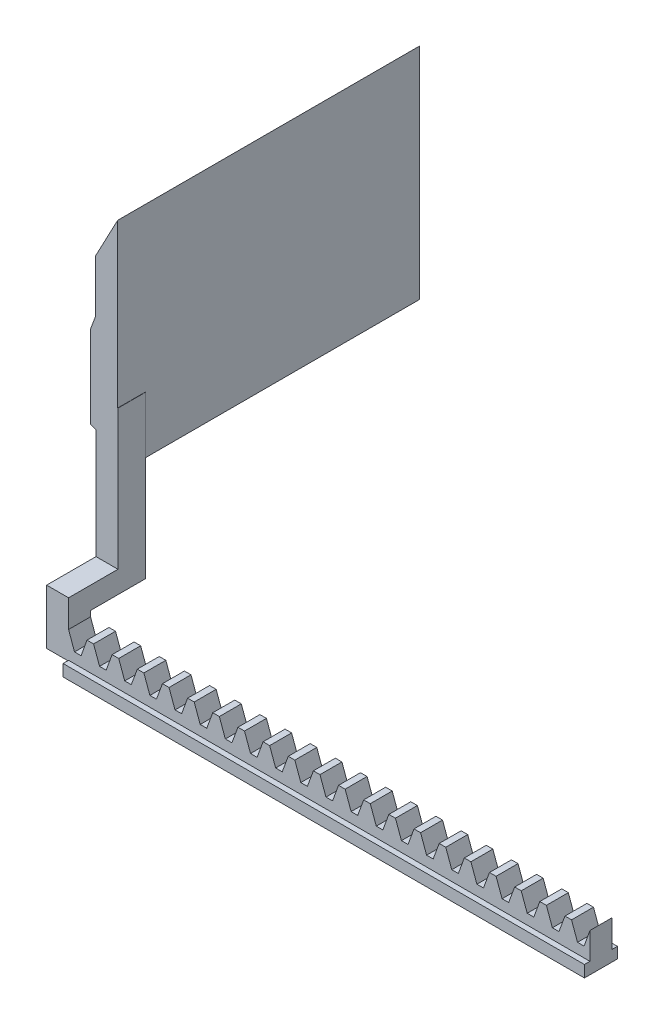
SolidWorks part; units mm, degrees
ref_plane "Plan de face" through (0, 0, 0) normal (0, 0, 1) x (1, 0, 0)
ref_plane "Plan de dessus" through (0, 0, 0) normal (0, 1, 0) x (1, 0, 0)
ref_plane "Plan de droite" through (0, 0, 0) normal (1, 0, 0) x (0, 0, -1)
sketch "Esquisse1" plane through (0, 0, 0) normal (0, 0, 1) x (1, 0, 0)
  line L0 (-0.6, 0) -> (0.6, 0)
  line L1 (0.6, 0) -> (1.6919, 3)
  line L2 (-0.6, 0) -> (-1.6919, 3)
  line L3 (-1.6919, 3) -> (-2.8919, 3)
  line L4 (1.6919, 3) -> (2.8919, 3)
  line L5 (0, 0) -> (0, 2.6442) construction
  line L6 (-47.5, -4) -> (47.5, -4)
  line L7 (3.9838, 0) -> (2.8919, 3)
  line L8 (5.1838, 0) -> (6.2757, 3)
  line L9 (3.9838, 0) -> (5.1838, 0)
  line L10 (8.5676, 0) -> (7.4757, 3)
  line L11 (9.7676, 0) -> (10.8596, 3)
  line L12 (8.5676, 0) -> (9.7676, 0)
  line L13 (13.1515, 0) -> (12.0596, 3)
  line L14 (14.3515, 0) -> (15.4434, 3)
  line L15 (13.1515, 0) -> (14.3515, 0)
  line L16 (17.7353, 0) -> (16.6434, 3)
  line L17 (18.9353, 0) -> (20.0272, 3)
  line L18 (17.7353, 0) -> (18.9353, 0)
  line L19 (22.3191, 0) -> (21.2272, 3)
  line L20 (23.5191, 0) -> (24.611, 3)
  line L21 (22.3191, 0) -> (23.5191, 0)
  line L22 (26.9029, 0) -> (25.811, 3)
  line L23 (28.1029, 0) -> (29.1948, 3)
  line L24 (26.9029, 0) -> (28.1029, 0)
  line L25 (31.4867, 0) -> (30.3948, 3)
  line L26 (32.6867, 0) -> (33.7787, 3)
  line L27 (31.4867, 0) -> (32.6867, 0)
  line L28 (36.0706, 0) -> (34.9787, 3)
  line L29 (37.2706, 0) -> (38.3625, 3)
  line L30 (36.0706, 0) -> (37.2706, 0)
  line L31 (40.6544, 0) -> (39.5625, 3)
  line L32 (41.8544, 0) -> (42.9463, 3)
  line L33 (40.6544, 0) -> (41.8544, 0)
  line L34 (45.2382, 0) -> (44.1463, 3)
  line L35 (46.4382, 0) -> (47.5, 3.0001)
  line L36 (45.2382, 0) -> (46.4382, 0)
  line L37 (-44.1463, 3) -> (-42.9463, 3)
  line L38 (-39.5625, 3) -> (-38.3625, 3)
  line L39 (-34.9787, 3) -> (-33.7787, 3)
  line L40 (-30.3948, 3) -> (-29.1948, 3)
  line L41 (-25.811, 3) -> (-24.611, 3)
  line L42 (-21.2272, 3) -> (-20.0272, 3)
  line L43 (-16.6434, 3) -> (-15.4434, 3)
  line L44 (-12.0596, 3) -> (-10.8596, 3)
  line L45 (-7.4757, 3) -> (-6.2757, 3)
  line L46 (-2.8919, 3) -> (2.8919, 3)
  line L47 (6.2757, 3) -> (7.4757, 3)
  line L48 (10.8596, 3) -> (12.0596, 3)
  line L49 (15.4434, 3) -> (16.6434, 3)
  line L50 (20.0272, 3) -> (21.2272, 3)
  line L51 (24.611, 3) -> (25.811, 3)
  line L52 (29.1948, 3) -> (30.3948, 3)
  line L53 (33.7787, 3) -> (34.9787, 3)
  line L54 (38.3625, 3) -> (39.5625, 3)
  line L55 (42.9463, 3) -> (44.1463, 3)
  line L56 (47.5, 3.0001) -> (47.5, -4)
  line L57 (-47.5, 3.0001) -> (-47.5, -4)
  line L64 (-5.1838, 0) -> (-6.2757, 3)
  line L65 (-5.1838, 0) -> (-3.9838, 0)
  line L66 (-3.9838, 0) -> (-2.8919, 3)
  line L67 (-9.7676, 0) -> (-10.8596, 3)
  line L68 (-9.7676, 0) -> (-8.5676, 0)
  line L69 (-8.5676, 0) -> (-7.4757, 3)
  line L70 (-14.3515, 0) -> (-15.4434, 3)
  line L71 (-14.3515, 0) -> (-13.1515, 0)
  line L72 (-13.1515, 0) -> (-12.0596, 3)
  line L73 (-18.9353, 0) -> (-20.0272, 3)
  line L74 (-18.9353, 0) -> (-17.7353, 0)
  line L75 (-17.7353, 0) -> (-16.6434, 3)
  line L76 (-23.5191, 0) -> (-24.611, 3)
  line L77 (-23.5191, 0) -> (-22.3191, 0)
  line L78 (-22.3191, 0) -> (-21.2272, 3)
  line L79 (-28.1029, 0) -> (-29.1948, 3)
  line L80 (-28.1029, 0) -> (-26.9029, 0)
  line L81 (-26.9029, 0) -> (-25.811, 3)
  line L82 (-32.6867, 0) -> (-33.7787, 3)
  line L83 (-32.6867, 0) -> (-31.4867, 0)
  line L84 (-31.4867, 0) -> (-30.3948, 3)
  line L85 (-37.2706, 0) -> (-38.3625, 3)
  line L86 (-37.2706, 0) -> (-36.0706, 0)
  line L87 (-36.0706, 0) -> (-34.9787, 3)
  line L88 (-41.8544, 0) -> (-42.9463, 3)
  line L89 (-41.8544, 0) -> (-40.6544, 0)
  line L90 (-40.6544, 0) -> (-39.5625, 3)
  line L91 (-46.421, -0.0046) -> (-47.5, 3.0001)
  line L92 (-46.421, -0.0046) -> (-45.221, -0.0098)
  line L93 (-45.221, -0.0098) -> (-44.1463, 3)
  point P4 (0, 0)
  point P14 (0, -4)
  dimension "D1" = 1.2
  dimension "D2" = 1.2
  dimension "D3" = 1.2
  dimension "D4" = 3
  dimension "D5" = 40
  dimension "D6" = 4
  dimension "D7" = 95
extrude "Boss.-Extru.1" add sketch "Esquisse1" against normal blind 4 contours L93 L92 L91 L57 L6 L56 L35 L36 L34 L55 L32 L33 L31 L54 L29 L30 L28 L53 L26 L27 L25 L52 L23 L24 L22 L51 L20 L21 L19 L50 L17 L18 L16 L49 L14 L15 L13 L48 L11 L12 L10 L47 L8 L9 L7 L4 L1 L0 L2 L3
sketch "Esquisse2" plane through (-47.5, 0, 0) normal (-1, 0, 0) x (0, 0, 1)
  line L1 (-4, -4) -> (-5, -4)
  line L2 (-4, -4) -> (-4, -2)
  line L3 (-4, -2) -> (-5, -2)
  line L4 (-5, -4) -> (-5, -2)
  line L5 (0, -4) -> (1, -4)
  line L6 (0, -4) -> (0, -1.869)
  line L7 (0, -1.869) -> (1, -1.869)
  line L8 (1, -4) -> (1, -1.869)
  dimension "D1" = 2
  dimension "D2" = 1
extrude "Boss.-Extru.2" add sketch "Esquisse2" against normal up to surface (95 mm away) up to face at (47.5, -0.5, -2)
sketch "Esquisse3" plane through (0, 0, -4) normal (0, 0, -1) x (-1, 0, 0)
  line L1 (47.5, -2) -> (51.5, -2)
  line L2 (47.5, -2) -> (47.5, 8)
  line L3 (47.5, 8) -> (51.5, 8)
  line L4 (51.5, -2) -> (51.5, 8)
  dimension "D1" = 10
  dimension "D2" = 4
extrude "Boss.-Extru.3" add sketch "Esquisse3" against normal up to surface (4 mm away) up to face at (0.0004, 1.4215, 0)
sketch "Esquisse4" plane through (-51.5, 0, 0) normal (-1, 0, 0) x (0, 0, 1)
  line L1 (-4, 8) -> (-14, 8)
  line L2 (-4, 8) -> (-4, 4)
  line L3 (-4, 4) -> (-14, 4)
  line L4 (-14, 8) -> (-14, 4)
  dimension "D1" = 4
  dimension "D2" = 10
extrude "Boss.-Extru.4" add sketch "Esquisse4" against normal up to surface (4 mm away) up to face at (-47.5, 5.5, -2)
sketch "Esquisse5" plane through (0, 0, -4) normal (0, 0, -1) x (-1, 0, 0)
  line L0 (0, 0) -> (0, 64.43) construction
  line L1 (47.5, 8) -> (47.5, 64.43) construction
  line L2 (0, 24.43) -> (76.6771, 24.43) construction
  circle A0 centre (0, 19.22) radius 19.22
  dimension "D1" = 38.44
  dimension "D2" = 64.43
  dimension "D3" = 40
sketch "Esquisse6" plane through (-51.5, 0, 0) normal (-1, 0, 0) x (0, 0, 1)
  line L1 (-14, 4) -> (-9, 4)
  line L2 (-14, 4) -> (-14, 33.43)
  line L3 (-14, 33.43) -> (-9, 33.43)
  line L4 (-9, 4) -> (-9, 33.43)
  dimension "D1" = 5
  dimension "D2" = 29.43
extrude "Boss.-Extru.5" add sketch "Esquisse6" against normal up to surface (4 mm away) up to face at (-47.5, 5, -6)
sketch "Esquisse7" plane through (0, 0, -14) normal (0, 0, -1) x (-1, 0, 0)
  line L0 (47.544, 63.0534) -> (47.544, 23.0534)
  line L3 (47.544, 23.0534) -> (51.55, 28.0534)
  line L4 (51.55, 28.0534) -> (52.544, 28.4234)
  line L5 (52.544, 28.4234) -> (52.544, 43.3034)
  line L6 (52.544, 43.3034) -> (51.55, 45.9734)
  line L7 (51.55, 45.9734) -> (51.55, 55.4943)
  line L8 (51.55, 55.4943) -> (47.544, 63.0534)
  dimension "D1" = 40
  dimension "D2" = 14.88
  dimension "D3" = 5
  dimension "D4" = 2.67
  dimension "D5" = 9.521
  dimension "D6" = 5
  dimension "D7" = 0.37
extrude "Boss.-Extru.6" add sketch "Esquisse7" along normal blind 50 and the other way blind 5
